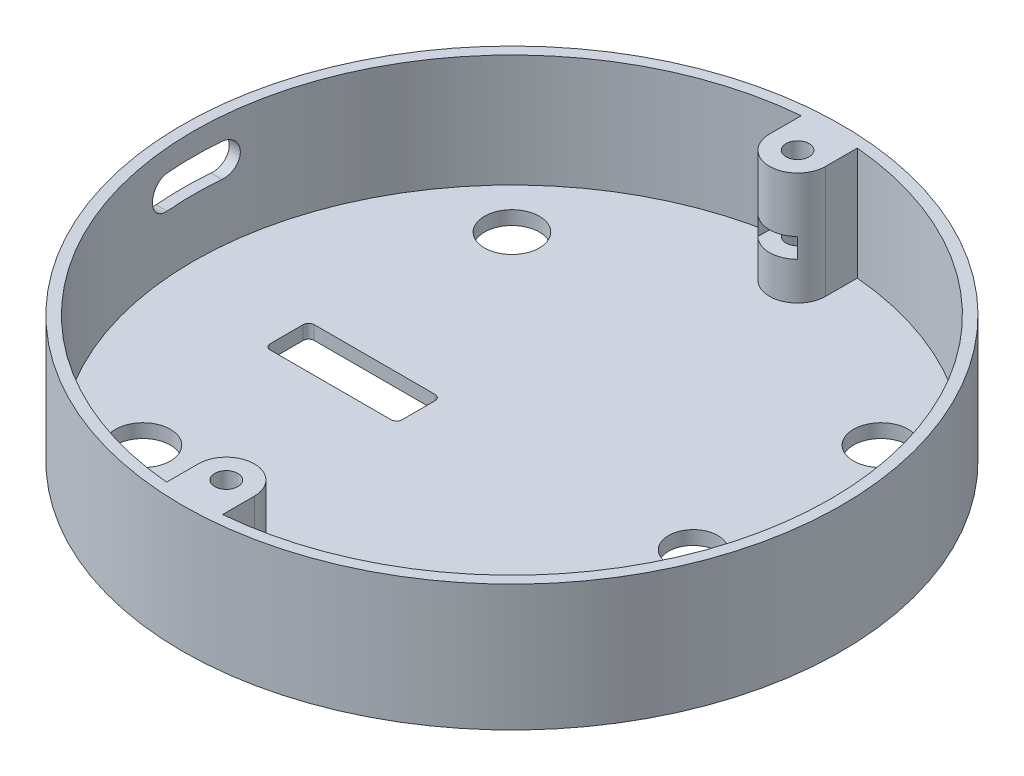
SolidWorks part; units mm, degrees
material "PLA+"
ref_plane "Front Plane" through (0, 0, 0) normal (0, 0, 1) x (1, 0, 0)
ref_plane "Top Plane" through (0, 0, 0) normal (0, 1, 0) x (1, 0, 0)
ref_plane "Right Plane" through (0, 0, 0) normal (1, 0, 0) x (0, 0, -1)
sketch "Sketch1" plane through (0, 0, 0) normal (0, 1, 0) x (1, 0, 0)
  circle A0 centre (0, 0) radius 60
  dimension "D1" = 120
extrude "Boss-Extrude1" add sketch "Sketch1" along normal blind 2.5
sketch "Sketch2" plane through (0, 2.5, 0) normal (0, 1, 0) x (1, 0, 0)
  circle A0 centre (0, 0) radius 58
  circle A1 centre (0, 0) radius 60
  circle A2 centre (0, 0) radius 60
  dimension "D1" = 0
  dimension "D2" = 2
extrude "Boss-Extrude2" add sketch "Sketch2" along normal blind 20.5
sketch "Sketch3" plane through (0, 2.5, 0) normal (0, 1, 0) x (1, 0, 0)
  line L0 (0, 0) -> (33, 0) construction
  line L1 (0, 0) -> (33.5876, 33.5876) construction
  circle A0 centre (33, 0) radius 4.5
  circle A1 centre (33.5876, 33.5876) radius 5
  circle A2 centre (33.5876, -33.5876) radius 5
  circle A3 centre (-33.5876, -33.5876) radius 5
  circle A4 centre (-33.5876, 33.5876) radius 5
  dimension "D4" = 9
  dimension "D5" = 10
  dimension "D1" = 45
  dimension "D2" = 47.5
  dimension "D3" = 33
  dimension "D6" = 4
extrude "Cut-Extrude1" cut sketch "Sketch3" against normal through all
sketch "Sketch4" plane through (0, 2.5, 0) normal (0, 1, 0) x (1, 0, 0)
  line L1 (-38, 1) -> (-14, 1)
  line L2 (-38, 1) -> (-38, -7)
  line L3 (-38, -7) -> (-14, -7)
  line L4 (-14, 1) -> (-14, -7)
  dimension "D1" = 14
  dimension "D2" = 24
  dimension "D3" = 8
  dimension "D4" = 1
extrude "Cut-Extrude2" cut sketch "Sketch4" against normal through all
fillet "Fillet1" radius 1 4 edges at (-14, 1.25, 7) (-38, 1.25, 7) (-14, 1.25, -1) (-38, 1.25, -1)
sketch "Sketch5" plane through (0, 2.5, 0) normal (0, 1, 0) x (1, 0, 0)
  line L0 (0, -52) -> (0, 52) construction
  line L1 (-5.1, 52) -> (-5.1, 57.7753)
  line L2 (5.1, 52) -> (5.1, 57.7753)
  line L3 (0, 0) -> (18.3005, 0) construction
  line L4 (5.1, -52) -> (5.1, -57.7753)
  line L5 (-5.1, -52) -> (-5.1, -57.7753)
  circle A0 centre (0, 52) radius 2.1
  arc A1 (-5.1, 52) -> (5.1, 52) centre (0, 52) ccw
  circle A2 centre (0, 0) radius 58 construction
  arc A3 (5.1, 57.7753) -> (-5.1, 57.7753) centre (0, 0) ccw
  circle A4 centre (0, 52) radius 5.1 construction
  arc A5 (5.1, -57.7753) -> (-5.1, -57.7753) centre (0, 0) cw
  arc A6 (-5.1, -52) -> (5.1, -52) centre (0, -52) cw
  circle A7 centre (0, -52) radius 2.1
  dimension "D2" = 4.2
  dimension "D1" = 52
  dimension "D3" = 3
extrude "Boss-Extrude3" add sketch "Sketch5" along normal through all
ref_plane "Plane1" through (0, 13, 0) normal (0, 1, 0) x (1, 0, 0)
sketch "Sketch6" plane through (0, 13, 0) normal (0, 1, 0) x (1, 0, 0)
  line L0 (0, 0) -> (7.9982, 0) construction
  line L1 (3.6, 54.0785) -> (0, 56.1569)
  line L2 (0, 56.1569) -> (-3.6, 54.0785)
  line L3 (-3.6, 54.0785) -> (-3.6, 48.3875)
  line L6 (3.6, 48.3875) -> (3.6, 54.0785)
  line L7 (-1.8, 48.8823) -> (0, 47.8431) [skipped]
  line L8 (1.8, 48.8823) -> (3.6, 49.9215) [skipped]
  line L9 (3.6, -48.3875) -> (3.6, -54.0785)
  line L10 (-3.6, -54.0785) -> (-3.6, -48.3875)
  line L11 (0, -56.1569) -> (-3.6, -54.0785)
  line L12 (3.6, -54.0785) -> (0, -56.1569)
  circle A0 centre (0, 52) radius 3.6 construction
  arc A1 (-5.1, 52) -> (5.1, 52) centre (0, 52) ccw construction
  arc A2 (-3.6, 48.3875) -> (3.6, 48.3875) centre (0, 52) ccw
  circle A3 centre (0, -52) radius 3.6 construction
  arc A4 (-3.6, -48.3875) -> (3.6, -48.3875) centre (0, -52) cw
  dimension "D1" = 7.2
extrude "Cut-Extrude3" cut sketch "Sketch6" against normal blind 3.6
ref_plane "Plane2" through (-60, 0, 0) normal (-1, 0, 0) x (0, 0, 1)
sketch "Sketch7" plane through (-60, 0, 0) normal (-1, 0, 0) x (0, 0, 1)
  line L0 (-5, 16) -> (5, 16) construction
  line L1 (-5, 19) -> (5, 19)
  line L2 (-5, 13) -> (5, 13)
  line L3 (60, 23) -> (-60, 23) construction
  arc A0 (-5, 19) -> (-5, 13) centre (-5, 16) ccw
  arc A1 (5, 13) -> (5, 19) centre (5, 16) ccw
  point P2 (0, 16)
  dimension "D1" = 3
  dimension "D2" = 10
  dimension "D3" = 4
extrude "Cut-Extrude4" cut sketch "Sketch7" against normal up to next
